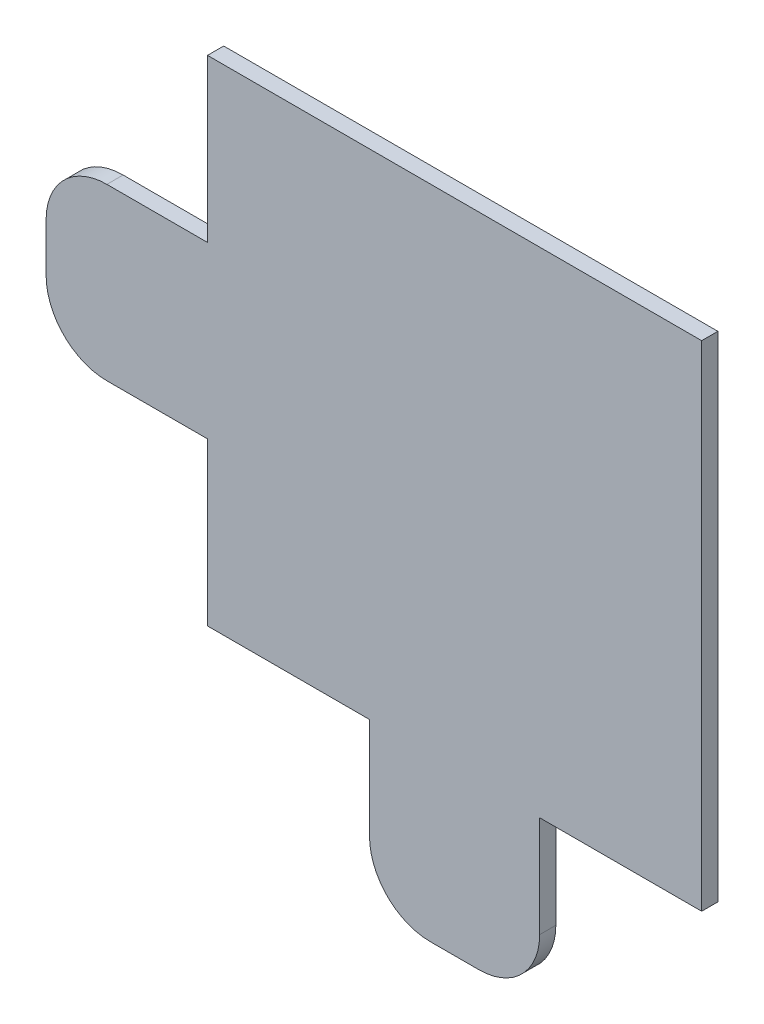
SolidWorks part; units mm, degrees
ref_plane "Front Plane" through (0, 0, 0) normal (0, 0, 1) x (1, 0, 0)
ref_plane "Top Plane" through (0, 0, 0) normal (0, 1, 0) x (1, 0, 0)
ref_plane "Right Plane" through (0, 0, 0) normal (1, 0, 0) x (0, 0, -1)
sketch "Sketch1" plane through (0, 0, 0) normal (0, 0, 1) x (1, 0, 0)
  line L0 (-0.305, 0.325) -> (-0.305, 0.125)
  line L1 (-0.4292, 0.125) -> (-0.305, 0.125)
  line L2 (-0.5042, 0.05) -> (-0.5042, -0.01)
  line L3 (-0.4292, -0.085) -> (-0.305, -0.085)
  line L4 (-0.305, -0.085) -> (-0.305, -0.285)
  line L5 (-0.305, -0.285) -> (-0.105, -0.285)
  line L6 (-0.105, -0.41) -> (-0.105, -0.285)
  line L7 (-0.03, -0.485) -> (0.03, -0.485)
  line L8 (0.105, -0.41) -> (0.105, -0.285)
  line L9 (0.105, -0.285) -> (0.305, -0.285)
  line L10 (0.305, 0.325) -> (0.305, -0.285)
  line L11 (-0.305, 0.325) -> (0.305, 0.325)
  line L13 (-0.33, 0.35) -> (-0.33, 0.15) construction
  line L14 (-0.4292, 0.15) -> (-0.33, 0.15) construction
  line L16 (-0.5292, 0.05) -> (-0.5292, -0.01) construction
  line L17 (-0.4292, -0.11) -> (-0.33, -0.11) construction
  line L18 (-0.33, -0.11) -> (-0.33, -0.31) construction
  line L19 (-0.33, -0.31) -> (-0.13, -0.31) construction
  line L20 (-0.13, -0.41) -> (-0.13, -0.31) construction
  line L21 (-0.03, -0.51) -> (0.03, -0.51) construction
  line L22 (0.13, -0.41) -> (0.13, -0.31) construction
  line L23 (0.13, -0.31) -> (0.33, -0.31) construction
  line L24 (0.33, 0.35) -> (0.33, -0.31) construction
  line L25 (-0.33, 0.35) -> (0.33, 0.35) construction
  arc A0 (-0.5042, 0.05) -> (-0.4292, 0.125) centre (-0.4292, 0.05) cw
  arc A1 (-0.4292, -0.085) -> (-0.5042, -0.01) centre (-0.4292, -0.01) cw
  arc A2 (-0.5292, 0.05) -> (-0.4292, 0.15) centre (-0.4292, 0.05) cw construction
  arc A3 (-0.13, -0.41) -> (-0.03, -0.51) centre (-0.03, -0.41) ccw construction
  arc A4 (0.13, -0.41) -> (0.03, -0.51) centre (0.03, -0.41) cw construction
  arc A5 (-0.105, -0.41) -> (-0.03, -0.485) centre (-0.03, -0.41) ccw
  arc A6 (0.105, -0.41) -> (0.03, -0.485) centre (0.03, -0.41) cw
  arc A7 (-0.4292, -0.11) -> (-0.5292, -0.01) centre (-0.4292, -0.01) cw construction
  point P0 (0, 0)
  point P5 (-0.3, 0)
  point P11 (0, -0.3)
  point P33 (-0.4992, 0.1)
  point P49 (0.1, -0.5)
  dimension "D3" = 0.1
  dimension "D10" = 0.1
  dimension "D11" = 0.1
  dimension "D4" = 0.1
  dimension "D2" = 0.35
  dimension "D5" = 0.31
  dimension "D6" = 0.025
extrude "Boss-Extrude1" add sketch "Sketch1" along normal mid plane 0.02
